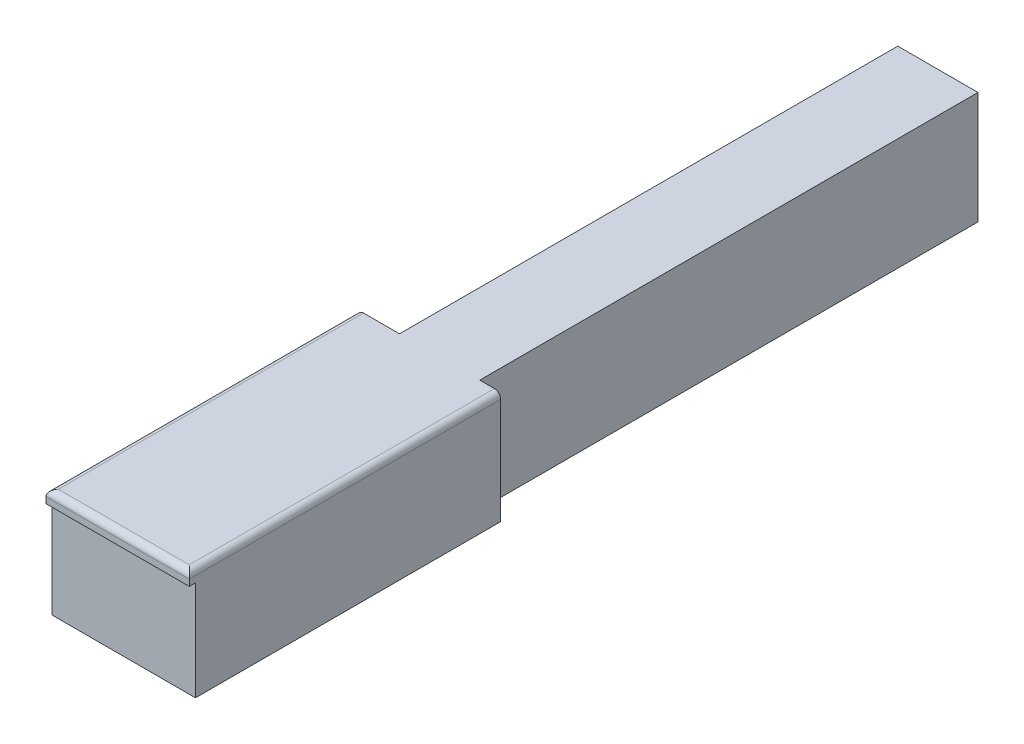
SolidWorks part; units mm, degrees
ref_plane "Alzado" through (0, 0, 0) normal (0, 0, 1) x (1, 0, 0)
ref_plane "Planta" through (0, 0, 0) normal (0, 1, 0) x (1, 0, 0)
ref_plane "Vista lateral" through (0, 0, 0) normal (1, 0, 0) x (0, 0, -1)
sketch "Croquis2" plane through (0, 0, 0) normal (0, 1, 0) x (1, 0, 0)
  line L1 (0, 0) -> (23, 0)
  line L2 (0, 0) -> (0, 130)
  line L3 (0, 130) -> (23, 130)
  line L4 (23, 0) -> (23, 130)
  line L5 (0, 130) -> (6.76, 130)
  line L6 (0, 115.866) -> (0, 50)
  line L7 (23, 130) -> (19.64, 130)
  line L8 (23, 130) -> (23, 50)
  line L9 (0, 50) -> (6.76, 50)
  line L10 (0, 130) -> (0, 50)
  line L11 (0, 50) -> (6.76, 50)
  line L12 (6.76, 130) -> (6.76, 50)
  line L13 (23, 50) -> (19.64, 50)
  line L14 (19.64, 130) -> (19.64, 50)
  dimension "D1" = 23
  dimension "D2" = 130
  dimension "D3" = 12.88
  dimension "D5" = 6.76
extrude "Saliente-Extruir1" add sketch "Croquis2" along normal blind 18 contours L14 L3 L2 L1 L4 L13
sketch "Croquis3" plane through (0, 0, 0) normal (0, 0, 1) x (1, 0, 0)
  line L0 (23, 18) -> (23, 0) construction
  line L1 (0, 0) -> (23, 0)
  line L2 (0, 0) -> (0, 16)
  line L3 (0, 16) -> (23, 16)
  line L4 (23, 0) -> (23, 16)
  line L5 (0, 18) -> (23, 18) construction
  dimension "D1" = 2
extrude "Cortar-Extruir1" cut sketch "Croquis3" against normal blind 1
fillet "Redondeo1" radius 1 3 edges at (11.5, 18, 0) (23, 18, -25) (0, 18, -25)
